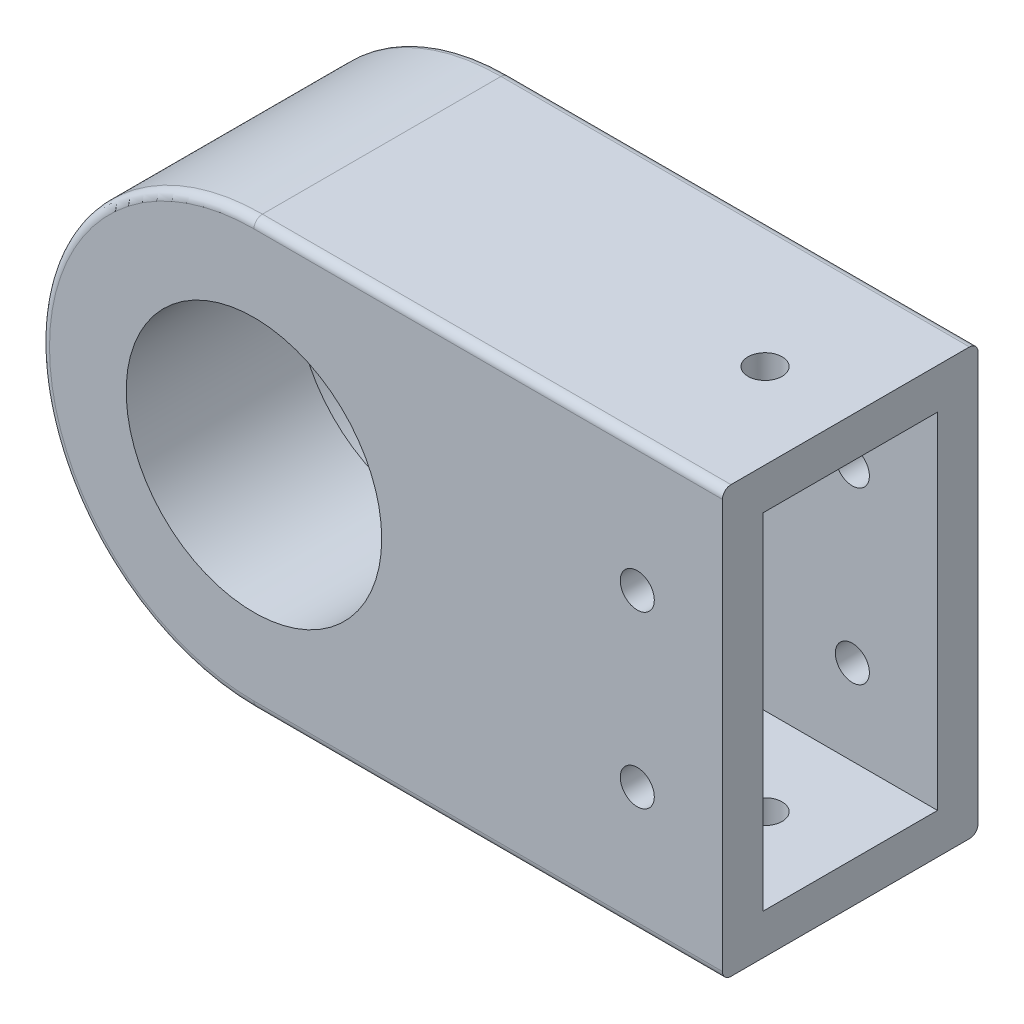
SolidWorks part; units mm, degrees
ref_plane "Front" through (0, 0, 0) normal (0, 0, 1) x (1, 0, 0)
ref_plane "Top" through (0, 0, 0) normal (0, 1, 0) x (1, 0, 0)
ref_plane "Right" through (0, 0, 0) normal (1, 0, 0) x (0, 0, -1)
sketch "Sketch1" plane through (0, 0, 0) normal (0, 0, 1) x (1, 0, 0)
  line L0 (0, 25) -> (70, 25)
  line L1 (70, 25) -> (70, -25)
  line L2 (70, -25) -> (0, -25)
  arc A0 (0, 25) -> (0, -25) centre (0, 0) ccw
extrude "Boss-Extrude2" add sketch "Sketch1" along normal blind 30
sketch "Sketch2" plane through (70, 0, 0) normal (1, 0, 0) x (0, 0, -1)
  line L0 (-30, 0) -> (0, 0) construction
  line L1 (-30, -25) -> (-30, 25) construction
  line L2 (0, -25) -> (0, 25) construction
  line L4 (-25.25, -20.25) -> (-4.75, -20.25)
  line L5 (-25.25, -20.25) -> (-25.25, 20.25)
  line L6 (-25.25, 20.25) -> (-4.75, 20.25)
  line L7 (-4.75, -20.25) -> (-4.75, 20.25)
  line L8 (-25.25, -20.25) -> (-4.75, 20.25) construction
  line L9 (-25.25, 20.25) -> (-4.75, -20.25) construction
  point P6 (-15, 0)
  point P7 (-15, 0)
sketch "Sketch3" plane through (0, 0, 30) normal (0, 0, 1) x (1, 0, 0)
  circle A0 centre (0, 0) radius 6.5
extrude "Cut-Extrude2" cut sketch "Sketch3" against normal blind 40
sketch "Sketch4" plane through (0, 0, 30) normal (0, 0, 1) x (1, 0, 0)
  circle A0 centre (0, 0) radius 19
extrude "Cut-Extrude3" cut sketch "Sketch4" against normal blind 25
extrude "Cut-Extrude5" cut sketch "Sketch2" against normal blind 50
sketch "Sketch6" plane through (0, 0, 30) normal (0, 0, 1) x (1, 0, 0)
  circle A0 centre (0, 0) radius 6.75
extrude "Cut-Extrude6" cut sketch "Sketch6" against normal blind 50
sketch "Sketch7" plane through (0, 0, 30) normal (0, 0, 1) x (1, 0, 0)
  circle A0 centre (0, 0) radius 19.25
extrude "Cut-Extrude7" cut sketch "Sketch7" against normal blind 25
sketch "Sketch8" plane through (70, 0, 0) normal (1, 0, 0) x (0, 0, -1)
  line L0 (-30, -25) -> (-30, 25)
  line L1 (-30, 25) -> (0, 25)
  line L2 (0, 25) -> (0, -25)
  line L3 (0, -25) -> (-30, -25)
extrude "Cut-Extrude8" cut sketch "Sketch8" against normal blind 15
sketch "Sketch9" plane through (0, 0, 4.75) normal (0, 0, 1) x (1, 0, 0)
  circle A0 centre (45, -10.25) radius 2
  circle A1 centre (45, 9.75) radius 2
extrude "Cut-Extrude9" cut sketch "Sketch9" against normal blind 15 and the other way blind 100
sketch "Sketch10" plane through (0, -20.25, 0) normal (0, 1, 0) x (1, 0, 0)
  circle A0 centre (45, -15) radius 2
extrude "Cut-Extrude10" cut sketch "Sketch10" against normal blind 15 and the other way blind 100
fillet "Fillet1" radius 1 6 edges at (27.5, 25, 0) (-25, 0, 0) (27.5, -25, 30) (-25, 0, 30) (27.5, -25, 0) (27.5, 25, 30)
sketch "Sketch12" plane through (0, 0, 5) normal (0, 0, 1) x (1, 0, 0)
  circle A0 centre (0, 0) radius 5
  circle A1 centre (0, 0) radius 6.75
extrude "Boss-Extrude3" add sketch "Sketch12" against normal blind 5
sketch "Sketch13" plane through (0, 0, 5) normal (0, 0, 1) x (1, 0, 0)
  circle A1 centre (-8, 0) radius 1
  circle A2 centre (0, 8) radius 1
  circle A3 centre (8, 0) radius 1
  circle A4 centre (0, -8) radius 1
extrude "Cut-Extrude11" cut sketch "Sketch13" against normal blind 5
sketch "Sketch14" plane through (0, 0, 30) normal (0, 0, 1) x (1, 0, 0)
  circle A0 centre (0, 0) radius 15
  circle A1 centre (0, 0) radius 19.25
extrude "Boss-Extrude4" add sketch "Sketch14" against normal blind 20
